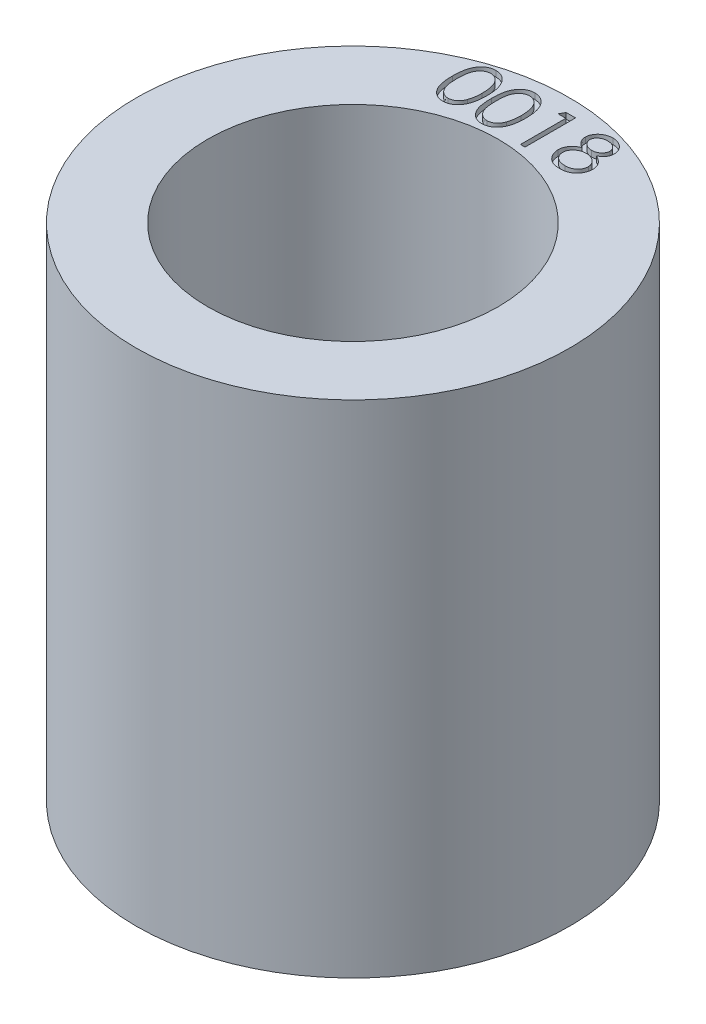
SolidWorks part; units mm, degrees
material "Nylon 101"
ref_plane "Front Plane" through (0, 0, 0) normal (0, 0, 1) x (1, 0, 0)
ref_plane "Top Plane" through (0, 0, 0) normal (0, 1, 0) x (1, 0, 0)
ref_plane "Right Plane" through (0, 0, 0) normal (1, 0, 0) x (0, 0, -1)
sketch "Sketch1" plane through (0, 0, 0) normal (0, 1, 0) x (1, 0, 0)
  circle A0 centre (0, 0) radius 3.81
  circle A1 centre (0, 0) radius 2.5527
  dimension "D1" = 7.62
  dimension "D2" = 5.1054
extrude "Boss-Extrude2" add sketch "Sketch1" along normal blind 8.8011
sketch "Sketch2" plane through (0, 8.8011, 0) normal (0, 1, 0) x (1, 0, 0)
  line L0 (-1.3978, 2.667) -> (1.6161, 2.667) construction
  circle A0 centre (0, 0) radius 2.5527 construction
  text T0 "0018" font "Century Gothic" height 0.889
  point P5 (-1.256, 2.667)
  point P6 (-1.3978, 2.667)
  dimension "D1" = 2.667
extrude "Cut-Extrude1" cut sketch "Sketch2" against normal blind 0.1016
